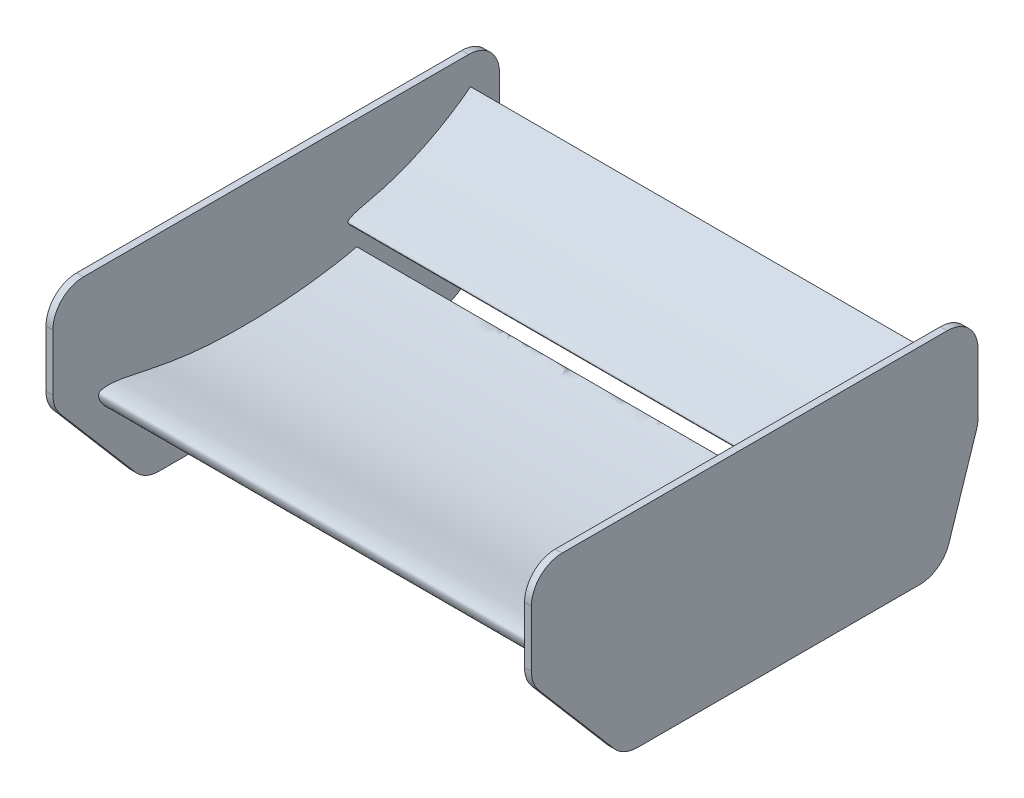
SolidWorks part; units mm, degrees
ref_plane "Front Plane" through (0, 0, 0) normal (0, 0, 1) x (1, 0, 0)
ref_plane "Top Plane" through (0, 0, 0) normal (0, 1, 0) x (1, 0, 0)
ref_plane "Right Plane" through (0, 0, 0) normal (1, 0, 0) x (0, 0, -1)
ref_plane "Soft Top Limit" through (0, 1174.6, 0) normal (0, 1, 0) x (1, 0, 0)
ref_plane "Soft Rear Limit" through (0, 0, -1192.975) normal (0, 0, 1) x (1, 0, 0)
ref_plane "Soft Right Limit" through (-501.65, 0, 0) normal (1, 0, 0) x (0, 0, -1)
ref_plane "Soft Left Limit" through (501.65, 0, 0) normal (1, 0, 0) x (0, 0, -1)
ref_plane "Soft Front Limit" through (0, 0, -165.1) normal (0, 0, 1) x (1, 0, 0)
ref_plane "Slant Limit" through (0, 528.6251, -619.2711) normal (0, -0.6492, 0.7606) x (1, 0, 0)
ref_plane "Bottom" through (0, 476.25, 0) normal (0, 1, 0) x (1, 0, 0)
ref_plane "Midplane" through (0, 0, 0) normal (1, 0, 0) x (0, 0, -1)
curve "Imported Airfoil Curve"
  spline degree 3 poles (0, 2520.0207, 6.126) (0, 2544.889, -1.81) (0, 2521.8965, 7.8839) (0, 2505.3253, 17.7145) (0, 2467.7144, 38.5723) (0, 2424.2142, 62.3813) (0, 2368.0949, 87.8078) (0, 2301.3729, 113.3478) (0, 2223.8362, 140.5377) (0, 2136.6129, 169.2441) (0, 2040.932, 199.097) (0, 1938.2341, 229.6055) (0, 1829.9414, 260.0781) (0, 1717.5266, 289.8586) (0, 1602.4273, 318.1375) (0, 1486.0259, 343.9752) (0, 1369.6902, 366.5754) (0, 1254.3666, 384.7865) (0, 1140.5393, 397.0034) (0, 1028.6357, 403.0127) (0, 919.0585, 402.9406) (0, 812.3986, 397.0375) (0, 709.2785, 385.5985) (0, 610.4299, 369.039) (0, 516.5862, 348.1086) (0, 428.5874, 323.3415) (0, 347.2653, 295.2055) (0, 273.332, 264.2656) (0, 207.4209, 231.0894) (0, 150.0337, 196.3024) (0, 101.596, 160.572) (0, 62.3674, 124.65) (0, 32.4977, 89.3959) (0, 12.0597, 55.6746) (0, 1.683, 26.6201) (0, -0.5567, 6.5526) (0, 0.5894, -3.9947) (0, 1.6947, -9.1451) (0, 2.8711, -12.4915) (0, 3.9449, -14.9776) (0, 4.8993, -16.669) (0, 5.9763, -18.2433) (0, 7.3264, -19.6365) (0, 8.8595, -20.9434) (0, 11.1868, -22.7306) (0, 14.6073, -24.7406) (0, 20.085, -27.4067) (0, 26.8353, -29.9257) (0, 44.6446, -35.1819) (0, 77.8093, -38.8998) (0, 130.2841, -38.2927) (0, 196.3018, -31.4611) (0, 276.2192, -18.4434) (0, 370.8288, 0.8611) (0, 480.7331, 24.811) (0, 605.9792, 50.0099) (0, 745.0759, 74.1542) (0, 895.4497, 95.0846) (0, 1053.6786, 110.004) (0, 1215.6439, 118.3392) (0, 1377.6893, 121.6348) (0, 1537.1174, 120.5125) (0, 1691.5141, 115.2051) (0, 1838.3121, 105.7388) (0, 1975.028, 93.0069) (0, 2099.5942, 78.4581) (0, 2210.5746, 63.1262) (0, 2306.3634, 48.0168) (0, 2387.2069, 33.7158) (0, 2449.0745, 22.0129) (0, 2499.1865, 10.4993) (0, 2520.0207, 6.126) (0, 2544.889, -1.81) (0, 2521.8965, 7.8839) knots -0.016237 -0.007308 -0.001841 0 0.001813 0.006911 0.014576 0.024172 0.035572 0.049013 0.064513 0.081849 0.100772 0.120997 0.142228 0.164173 0.186537 0.209023 0.231367 0.25332 0.274804 0.295858 0.316449 0.336531 0.356033 0.374893 0.39299 0.410197 0.426388 0.441459 0.455334 0.467938 0.479236 0.489204 0.497851 0.505194 0.511308 0.515097 0.516441 0.517273 0.51806 0.518436 0.518797 0.519154 0.519508 0.519887 0.520289 0.52116 0.522116 0.52372 0.525214 0.532575 0.542381 0.554776 0.569931 0.588005 0.609188 0.633329 0.660001 0.688743 0.718873 0.749543 0.780127 0.810209 0.839387 0.867183 0.893104 0.91676 0.937874 0.956199 0.971544 0.983763 0.992692 0.998159 1 1.001813 1.006911 1.014576 periodic
sketch "Airfoils Sketch" plane through (0, 0, 0) normal (1, 0, 0) x (0, 0, -1)
  line L0 (165.1, 1174.6) -> (165.1, 1060.6753) construction
  line L1 (165.1, 1060.6753) -> (663.9798, 476.25) construction
  line L2 (663.9798, 476.25) -> (1192.975, 476.25) construction
  line L3 (1192.975, 476.25) -> (1192.975, 1174.6) construction
  line L4 (1192.975, 1174.6) -> (165.1, 1174.6) construction
  line L5 (509.9361, 1174.6) -> (-509.9361, 1174.6) construction
  line L6 (165.1, 67.0076) -> (165.1, -67.0076) construction
  line L7 (364.7288, 826.8151) -> (873.8134, 230.4351) construction
  line L8 (279.3831, 476.25) -> (-279.3831, 476.25) construction
  line L9 (1192.975, 353.2696) -> (1192.975, -353.2696) construction
  line L10 (364.5896, 868.5327) -> (364.5896, 1023.4673) construction
  line L11 (897.9896, 878.5574) -> (897.9896, 1013.4426) construction
  line L12 (897.9896, 946) -> (364.5896, 946) construction
  line L13 (262.9896, 946) -> (1192.975, 946) construction
  line L14 (855.8887, 1048.5614) -> (904.1623, 945.0386) construction
  line L15 (1108.8736, 1167.1505) -> (1157.6222, 1062.6086) construction
  line L16 (1133.2479, 1114.8795) -> (880.0255, 996.8) construction
  line L21 (176.2614, 1047.6) -> (1192.975, 1047.6) construction
  spline S0 degree 3 poles (893.7912, 944.7229) (899.0172, 946.3778) (894.1843, 944.3529) (890.6998, 942.2962) (882.7919, 937.9336) (873.6459, 932.9541) (861.8492, 927.6408) (847.826, 922.3086) (831.5308, 916.6349) (813.2009, 910.6474) (793.0943, 904.4229) (771.5139, 898.0641) (748.7586, 891.7155) (725.138, 885.5141) (700.9544, 879.6292) (676.4985, 874.2577) (652.0578, 869.5659) (627.8318, 865.7954) (603.9228, 863.283) (580.4206, 862.0732) (557.4098, 862.1394) (535.0144, 863.4287) (513.3649, 865.8789) (492.6147, 869.4025) (472.9176, 873.8415) (454.4497, 879.0835) (437.3855, 885.0299) (421.8742, 891.5616) (408.0485, 898.5592) (396.0136, 905.8911) (385.8586, 913.417) (377.6374, 920.9787) (371.3813, 928.3959) (367.1052, 935.4868) (364.9396, 941.5929) (364.4786, 945.8081) (364.7242, 948.0225) (364.9587, 949.1035) (365.2073, 949.8057) (365.434, 950.3273) (365.6352, 950.682) (365.8621, 951.0121) (366.1463, 951.304) (366.4688, 951.5778) (366.9584, 951.952) (367.6776, 952.3725) (368.8291, 952.9298) (370.2479, 953.4556) (373.9902, 954.5511) (380.9564, 955.3164) (391.9757, 955.1645) (405.8359, 953.6991) (422.6123, 950.9282) (442.4709, 946.8302) (465.5393, 941.7496) (491.8288, 936.3995) (521.0273, 931.2645) (552.5956, 926.7991) (585.8161, 923.5923) (619.8244, 921.7664) (653.8518, 920.9989) (687.3317, 921.1602) (719.7569, 922.2028) (750.5884, 924.1223) (779.3042, 926.7322) (805.4694, 929.7293) (828.782, 932.8973) (848.9044, 936.0255) (865.8879, 938.991) (878.8853, 941.4197) (889.4141, 943.8142) (893.7912, 944.7229) (899.0172, 946.3778) (894.1843, 944.3529) knots -0.016237 -0.007308 -0.001841 0 0.001813 0.006911 0.014576 0.024172 0.035572 0.049013 0.064513 0.081849 0.100772 0.120997 0.142228 0.164173 0.186537 0.209023 0.231367 0.25332 0.274804 0.295858 0.316449 0.336531 0.356033 0.374893 0.39299 0.410197 0.426388 0.441459 0.455334 0.467938 0.479236 0.489204 0.497851 0.505194 0.511308 0.515097 0.516441 0.517273 0.51806 0.518436 0.518797 0.519154 0.519508 0.519887 0.520289 0.52116 0.522116 0.52372 0.525214 0.532575 0.542381 0.554776 0.569931 0.588005 0.609188 0.633329 0.660001 0.688743 0.718873 0.749543 0.780127 0.810209 0.839387 0.867183 0.893104 0.91676 0.937874 0.956199 0.971544 0.983763 0.992692 0.998159 1 1.001813 1.006911 1.014576 only from (897.9896, 946) to (897.9896, 946)
  spline S1 degree 3 poles (1131.5375, 1113.3438) (1133.6521, 1115.2864) (1131.806, 1113.2552) (1130.6071, 1111.5075) (1127.8187, 1107.6858) (1124.5791, 1103.2972) (1120.1551, 1098.1634) (1114.6782, 1092.5276) (1108.1983, 1086.2269) (1100.822, 1079.3267) (1092.6546, 1071.9207) (1083.8174, 1064.1247) (1074.4201, 1056.0734) (1064.5795, 1047.9005) (1054.4014, 1039.7532) (1043.9805, 1031.7893) (1033.4164, 1024.1515) (1022.7502, 1016.9986) (1011.956, 1010.5131) (1001.0665, 1004.736) (990.1279, 999.6735) (979.2106, 995.3279) (968.3905, 991.6985) (957.7597, 988.7777) (947.4262, 986.5247) (937.4984, 984.925) (928.0811, 983.9704) (919.2715, 983.6375) (911.1589, 983.8989) (903.8225, 984.7154) (897.3355, 986.0401) (891.7587, 987.81) (887.1468, 989.9462) (883.547, 992.3659) (881.1672, 994.7853) (880.0153, 996.6843) (879.6417, 997.7899) (879.5137, 998.355) (879.4763, 998.7434) (879.4684, 999.0412) (879.4854, 999.2542) (879.52, 999.4611) (879.5903, 999.6626) (879.6829, 999.864) (879.8324, 1000.15) (880.0808, 1000.5088) (880.5041, 1001.0283) (881.0612, 1001.592) (882.5953, 1002.9405) (885.733, 1004.8459) (890.9978, 1007.2132) (897.9021, 1009.5858) (906.4798, 1011.9841) (916.8145, 1014.4348) (928.8905, 1017.1296) (942.5554, 1020.4095) (957.5536, 1024.4354) (973.5286, 1029.3038) (990.0094, 1035.1356) (1006.5584, 1041.7972) (1022.8822, 1048.9655) (1038.7405, 1056.4536) (1053.903, 1064.1266) (1068.1148, 1071.863) (1081.1694, 1079.4589) (1092.9274, 1086.674) (1103.2934, 1093.3387) (1112.1536, 1099.2783) (1119.5597, 1104.4457) (1125.1924, 1108.476) (1129.6607, 1111.9435) (1131.5375, 1113.3438) (1133.6521, 1115.2864) (1131.806, 1113.2552) knots -0.016237 -0.007308 -0.001841 0 0.001813 0.006911 0.014576 0.024172 0.035572 0.049013 0.064513 0.081849 0.100772 0.120997 0.142228 0.164173 0.186537 0.209023 0.231367 0.25332 0.274804 0.295858 0.316449 0.336531 0.356033 0.374893 0.39299 0.410197 0.426388 0.441459 0.455334 0.467938 0.479236 0.489204 0.497851 0.505194 0.511308 0.515097 0.516441 0.517273 0.51806 0.518436 0.518797 0.519154 0.519508 0.519887 0.520289 0.52116 0.522116 0.52372 0.525214 0.532575 0.542381 0.554776 0.569931 0.588005 0.609188 0.633329 0.660001 0.688743 0.718873 0.749543 0.780127 0.810209 0.839387 0.867183 0.893104 0.91676 0.937874 0.956199 0.971544 0.983763 0.992692 0.998159 1 1.001813 1.006911 1.014576 only from (1133.2479, 1114.8795) to (1133.2479, 1114.8795)
  dimension "D1" = 533.4
  dimension "D2" = 228.6
  dimension "D3" = 0
  dimension "D4" = 101.6
  dimension "D5" = 279.4
  dimension "D6" = 59.7205
  dimension "D7" = 25
extrude "Extruded Airfoils" add sketch "Airfoils Sketch" along normal offset from surface (487.45 mm away) 14.2 up to plane "Soft Left Limit"
sketch "Endplate Sketch" plane through (501.65, 0, 0) normal (1, 0, 0) x (0, 0, -1)
  line L6 (333.4477, 1174.6) -> (1129.475, 1174.6)
  line L7 (1192.975, 1174.6) -> (165.1, 1174.6) construction
  line L8 (1192.975, 1111.1) -> (1192.975, 986.6717)
  line L9 (1192.975, 476.25) -> (1192.975, 1174.6) construction
  line L11 (1189.8464, 966.9854) -> (1132.8969, 792.34)
  line L12 (1072.5255, 748.5263) -> (489.1772, 748.5263)
  line L19 (440.8805, 770.7991) -> (285.151, 953.2323)
  line L26 (269.9477, 994.4595) -> (269.9477, 1111.1)
  line L28 (165.1, 1060.6753) -> (663.9798, 476.25) construction
  arc A12 (1129.475, 1174.6) -> (1192.975, 1111.1) centre (1129.475, 1111.1) cw
  arc A13 (1192.975, 986.6717) -> (1189.8464, 966.9854) centre (1129.475, 986.6717) cw
  arc A14 (1132.8969, 792.34) -> (1072.5255, 748.5263) centre (1072.5255, 812.0263) cw
  arc A15 (489.1772, 748.5263) -> (440.8805, 770.7991) centre (489.1772, 812.0263) cw
  arc A16 (285.151, 953.2323) -> (269.9477, 994.4595) centre (333.4477, 994.4595) cw
  arc A17 (333.4477, 1174.6) -> (269.9477, 1111.1) centre (333.4477, 1111.1) ccw
  point P16 (1192.975, 1174.6)
  point P19 (1192.975, 976.5799)
  point P29 (269.9477, 1174.6)
  dimension "D1" = 63.5
extrude "Extruded Endplate" add sketch "Endplate Sketch" against normal up to surface (14.2 mm away)
mirror "Mirror" about plane through (0, 0, 0) normal (1, 0, 0) of bodies 106
